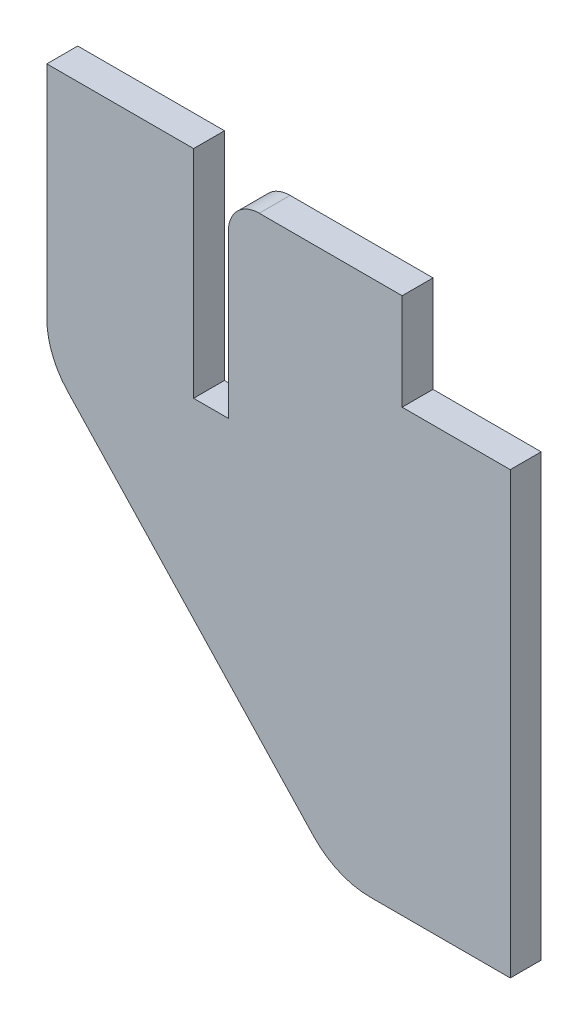
SolidWorks part; units mm, degrees
material "Q355"
ref_plane "前视基准面" through (0, 0, 0) normal (0, 0, 1) x (1, 0, 0)
ref_plane "上视基准面" through (0, 0, 0) normal (0, 1, 0) x (1, 0, 0)
ref_plane "右视基准面" through (0, 0, 0) normal (1, 0, 0) x (0, 0, -1)
sketch "草图1" plane through (0, 0, 0) normal (0, 0, 1) x (1, 0, 0)
  line L0 (0, 0) -> (0, 114)
  line L1 (0, 0) -> (-45, 0)
  line L2 (-45, 0) -> (-120, 80)
  line L3 (-120, 80) -> (-120, 145)
  line L4 (-120, 145) -> (-82, 145)
  line L5 (-82, 145) -> (-82, 89)
  line L6 (-82, 89) -> (-73, 89)
  line L7 (-73, 89) -> (-73, 131)
  line L8 (-65, 139) -> (-28, 139)
  line L9 (-28, 139) -> (-28, 114)
  line L10 (-28, 114) -> (0, 114)
  arc A0 (-65, 139) -> (-73, 131) centre (-65, 131) ccw
  point P15 (-73, 139)
  dimension "D10" = 8
  dimension "D1" = 120
  dimension "D2" = 145
  dimension "D3" = 65
  dimension "D4" = 45
  dimension "D5" = 73
  dimension "D6" = 56
  dimension "D7" = 9
  dimension "D8" = 50
  dimension "D9" = 45
  dimension "D11" = 25
extrude "凸台-拉伸1" add sketch "草图1" along normal blind 8
fillet "圆角1" radius 20 2 edges at (-45, 0, 4) (-120, 80, 4)
